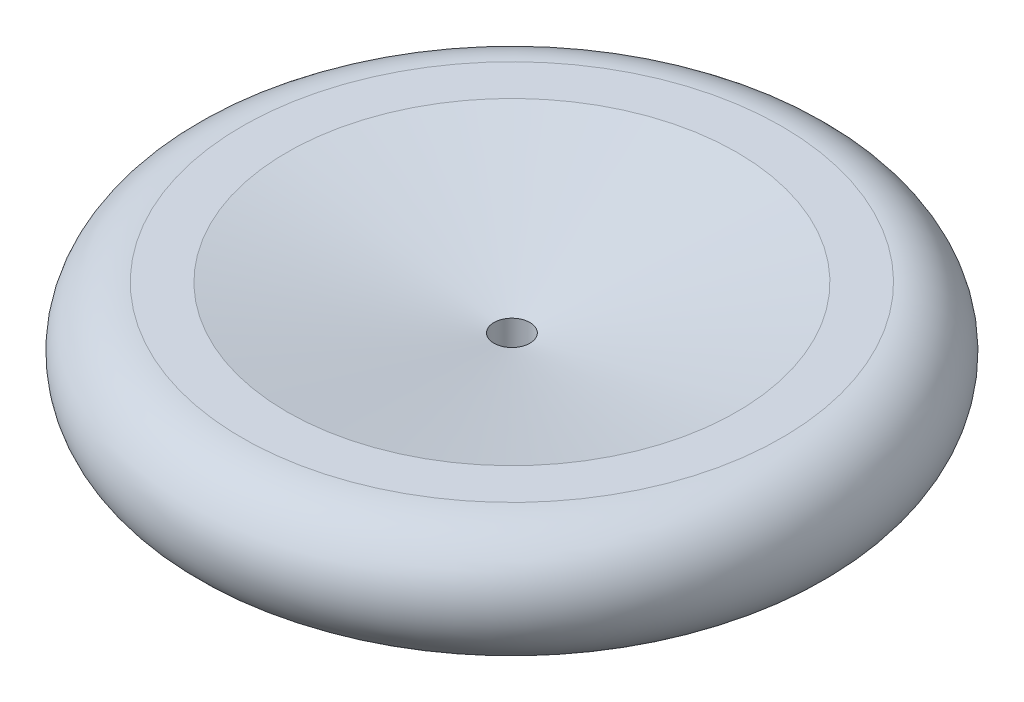
SolidWorks part; units mm, degrees
ref_plane "Front Plane" through (0, 0, 0) normal (0, 0, 1) x (1, 0, 0)
ref_plane "Top Plane" through (0, 0, 0) normal (0, 1, 0) x (1, 0, 0)
ref_plane "Right Plane" through (0, 0, 0) normal (1, 0, 0) x (0, 0, -1)
sketch "Sketch1" plane through (0, 0, 0) normal (0, 0, 1) x (1, 0, 0)
  line L0 (0, 0) -> (60, 0) construction
  line L1 (0, 0) -> (0, 35.6512) construction
  line L2 (4, 0) -> (4, 3.5)
  line L3 (50, 13.2776) -> (60, 13.2776)
  line L4 (4, 3.5) -> (50, 13.2776)
  line L5 (50, -13.2776) -> (60, -13.2776)
  line L6 (4, -3.5) -> (50, -13.2776)
  line L7 (4, -3.5) -> (4, 0)
  arc A0 (60, -13.2776) -> (60, 13.2776) centre (60, 0) ccw
  point P13 (0, 0)
  dimension "D1" = 60
  dimension "D2" = 50
  dimension "D3" = 8
  dimension "D4" = 12
  dimension "D5" = 3.5
revolve "Revolve1" add sketch "Sketch1" angle 360 about L1
